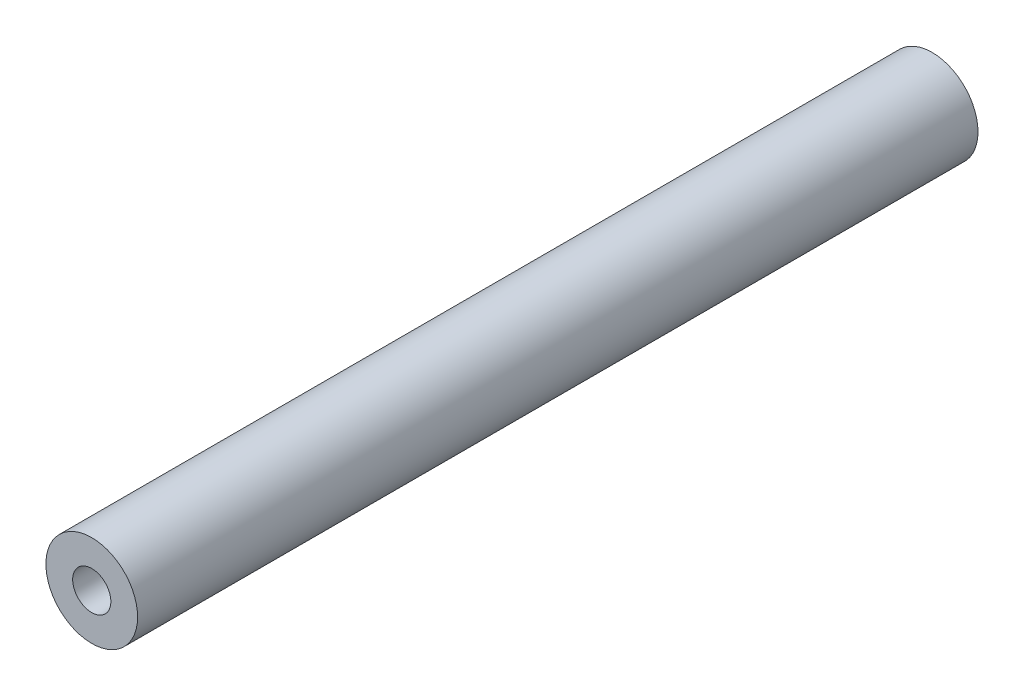
SolidWorks part; units mm, degrees
material "Liga 1060"
ref_plane "Plano frontal" through (0, 0, 0) normal (0, 0, 1) x (1, 0, 0)
ref_plane "Plano superior" through (0, 0, 0) normal (0, 1, 0) x (1, 0, 0)
ref_plane "Plano direito" through (0, 0, 0) normal (1, 0, 0) x (0, 0, -1)
sketch "Esboço1" plane through (0, 0, 0) normal (0, 0, 1) x (1, 0, 0)
  circle A0 centre (0, 0) radius 3
  dimension "D1" = 6
extrude "Ressalto-extrusão1" add sketch "Esboço1" along normal blind 55
hole_wizard "Broca de rosquear para tarraxa de M32" positions "3DSketch3" profile "Esboço3" hole size "M3" standard "ISO"
sketch3d "3DSketch3"
  point P0 (0, 0, 55)
sketch "Esboço3" plane through (0, 0, 55) normal (1, 0, 0) x (0, -1, 0)
  line L0 (0, 0) -> (0, 4.7511)
  line L1 (0, 4.7511) -> (1.25, 4)
  line L2 (1.25, 4) -> (1.25, 0)
  line L5 (1.25, 0) -> (0, 0)
  line L10 (0, 4.7511) -> (-1.25, 4) construction
  line L11 (0, -6.35) -> (0, 107.95) construction
  dimension "Hole Dia." = 2.5
  dimension "Hole Depth" = 4
  dimension "Drill Angle" = 118
hole_wizard "Broca de rosquear para tarraxa de M31" positions "Esboço4" profile "Esboço5" hole size "M3" standard "ISO"
sketch "Esboço4" plane through (0, 0, 0) normal (0, 0, -1) x (-1, 0, 0)
  point P0 (0, 0)
sketch "Esboço5" plane through (0, 0, 0) normal (1, 0, 0) x (0, 1, 0)
  line L0 (0, 0) -> (0, 4.7511)
  line L1 (0, 4.7511) -> (1.25, 4)
  line L2 (1.25, 4) -> (1.25, 0)
  line L5 (1.25, 0) -> (0, 0)
  line L10 (0, 4.7511) -> (-1.25, 4) construction
  line L11 (0, -6.35) -> (0, 107.95) construction
  dimension "Hole Dia." = 2.5
  dimension "Hole Depth" = 4
  dimension "Drill Angle" = 118
